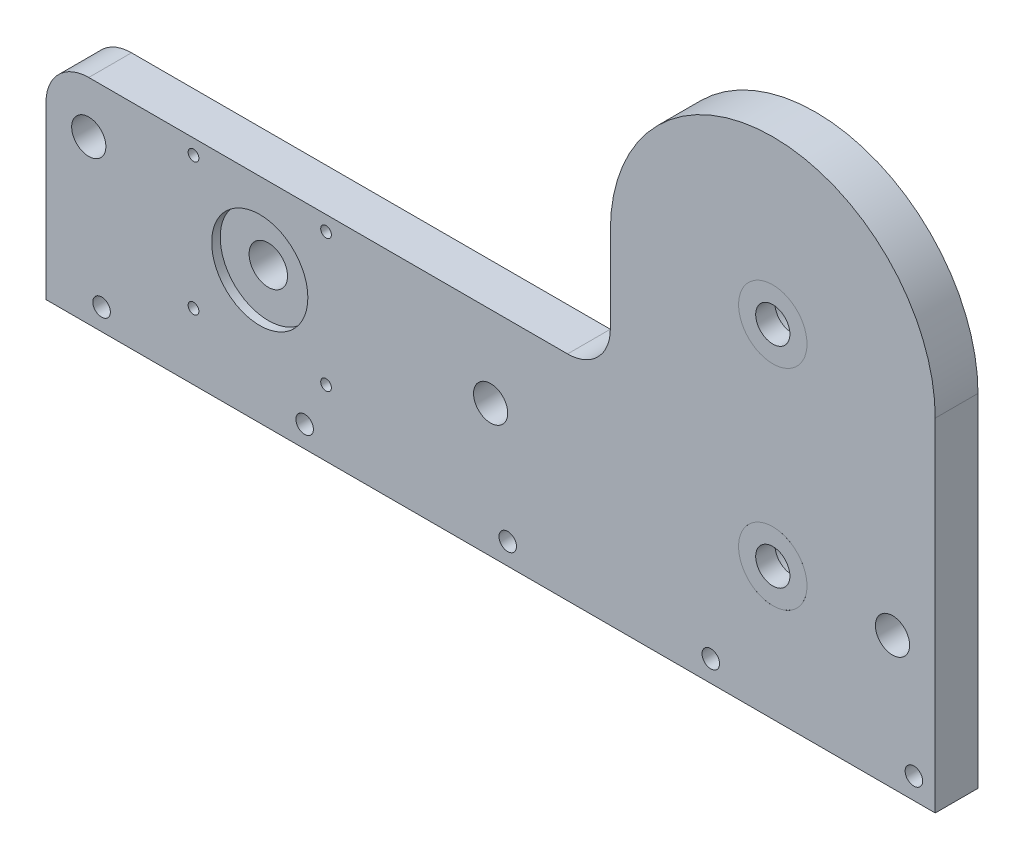
SolidWorks part; units mm, degrees
material "PTEG"
ref_plane "Alzado" through (0, 0, 0) normal (0, 0, 1) x (1, 0, 0)
ref_plane "Planta" through (0, 0, 0) normal (0, 1, 0) x (1, 0, 0)
ref_plane "Vista lateral" through (0, 0, 0) normal (1, 0, 0) x (0, 0, -1)
sketch "Croquis1" plane through (0, 0, 0) normal (0, 0, 1) x (1, 0, 0)
  line L0 (0, 0) -> (208, 0)
  line L1 (208, 0) -> (208, 80)
  line L2 (0, 0) -> (0, 40)
  line L3 (10, 50) -> (122, 50)
  line L4 (132, 60) -> (132, 80)
  arc A0 (208, 80) -> (132, 80) centre (170, 80) ccw
  arc A1 (0, 40) -> (10, 50) centre (10, 40) cw
  arc A2 (122, 50) -> (132, 60) centre (122, 60) ccw
  circle A3 centre (170, 80) radius 8
  circle A4 centre (50, 31) radius 4.5
  circle A5 centre (65.5, 46.5) radius 1.25
  circle A6 centre (34.5, 46.5) radius 1.25
  circle A7 centre (34.5, 15.5) radius 1.25
  circle A8 centre (65.5, 15.5) radius 1.25
  dimension "D4" = 80
  dimension "D5" = 10
  dimension "D6" = 16
  dimension "D9" = 9
  dimension "D12" = 2.5
  dimension "D15" = 31
  dimension "D16" = 31
  dimension "D17" = 21.9203
  dimension "D1" = 50
  dimension "D2" = 208
  dimension "D3" = 76
  dimension "D7" = 31
  dimension "D8" = 50
  dimension "D10" = 15.5
  dimension "D11" = 15.5
  dimension "D13" = 2
  dimension "D14" = 2
extrude "Saliente-Extruir1" add sketch "Croquis1" against normal blind 10
sketch "Croquis2" plane through (0, 0, 0) normal (0, 0, 1) x (1, 0, 0)
  circle A0 centre (50, 31) radius 11.25
  dimension "D1" = 22.5
extrude "Cortar-Extruir1" cut sketch "Croquis2" against normal blind 2
sketch "Croquis3" plane through (0, 0, -10) normal (0, 0, -1) x (-1, 0, 0)
  line L0 (0, 0) -> (-208, 0) construction
  line L1 (-208, 0) -> (-208, 80) construction
  line L2 (-170, 80) -> (-170, 0) construction
  circle A0 centre (-170, 31) radius 8
  dimension "D2" = 16
  dimension "D3" = 38
  dimension "D1" = 31
extrude "Cortar-Extruir2" cut sketch "Croquis3" against normal blind 10
sketch "Croquis4" plane through (0, 0, -10) normal (0, 0, -1) x (-1, 0, 0)
  line L0 (-208, 0) -> (-208, 80) construction
  line L1 (0, 0) -> (-208, 0) construction
  circle A0 centre (-203, 5) radius 2.05
  circle A1 centre (-155.5, 5) radius 2.05
  circle A2 centre (-108, 5) radius 2.05
  circle A3 centre (-60.5, 5) radius 2.05
  circle A4 centre (-13, 5) radius 2.05
  dimension "D3" = 4.1
  dimension "D1" = 5
  dimension "D2" = 5
  dimension "D4" = 5
extrude "Cortar-Extruir3" cut sketch "Croquis4" against normal through all
sketch "Croquis6" plane through (0, 0, 0) normal (0, 0, 1) x (1, 0, 0)
  circle A0 centre (170, 31) radius 8
  circle A1 centre (170, 31) radius 4
  circle A2 centre (170, 80) radius 8
  circle A3 centre (170, 80) radius 4
  dimension "D1" = 8
  dimension "D2" = 16
  dimension "D3" = 16
  dimension "D4" = 8
extrude "Saliente-Extruir2" add sketch "Croquis6" against normal blind 4.5 separate body
sketch "Croquis7" plane through (0, 0, -10) normal (0, 0, -1) x (-1, 0, 0)
  line L0 (-208, 31) -> (0, 31) construction
  line L1 (-208, 0) -> (-208, 80) construction
  line L2 (0, 40) -> (0, 0) construction
  line L3 (0, 0) -> (-208, 0) construction
  line L4 (-122, 50) -> (-10, 50) construction
  circle A0 centre (-198, 31) radius 4
  circle A1 centre (-104, 31) radius 4
  circle A2 centre (-10, 38) radius 4
  point P15 (-104, 0)
  point P16 (0, 0)
  dimension "D1" = 8
  dimension "D2" = 8
  dimension "D3" = 8
  dimension "D5" = 10
  dimension "D6" = 12
  dimension "D4" = 10
extrude "Cortar-Extruir4" cut sketch "Croquis7" against normal through all
